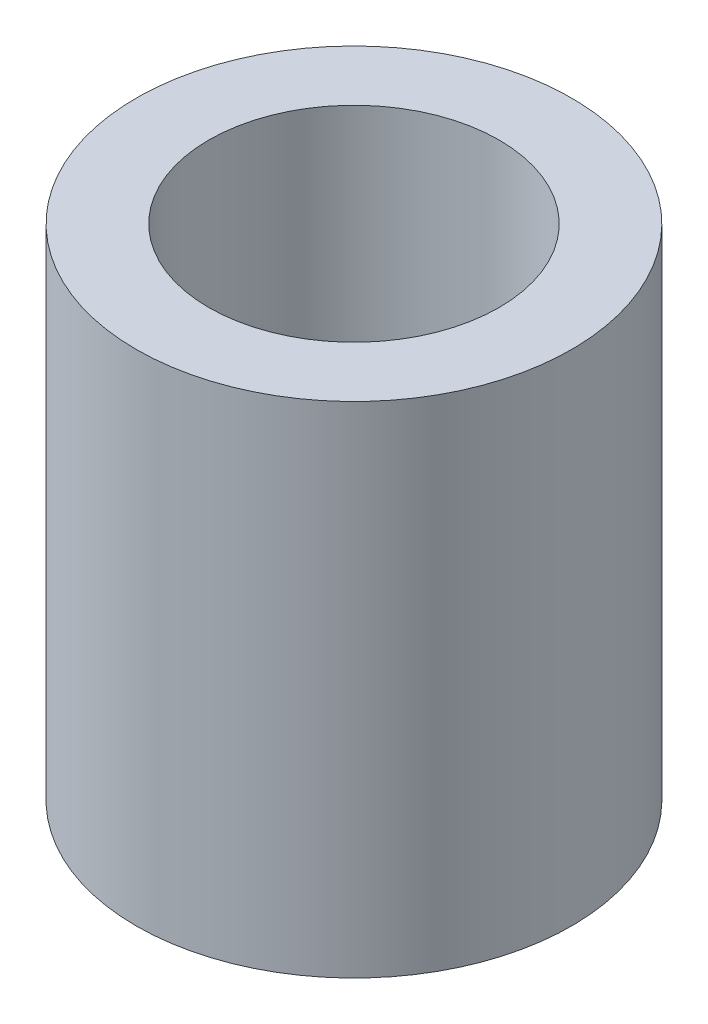
SolidWorks part; units mm, degrees
material "Delrin 2700 NC010, Low Viscosity Acetal Copolymer (SS)"
ref_plane "Front Plane" through (0, 0, 0) normal (0, 0, 1) x (1, 0, 0)
ref_plane "Top Plane" through (0, 0, 0) normal (0, 1, 0) x (1, 0, 0)
ref_plane "Right Plane" through (0, 0, 0) normal (1, 0, 0) x (0, 0, -1)
sketch "Sketch1" plane through (0, 0, 0) normal (0, 1, 0) x (1, 0, 0)
  circle A0 centre (-45.8833, 24.5388) radius 6.35
  circle A1 centre (-45.8833, 24.5388) radius 9.525
  dimension "D1" = 12.7
  dimension "D2" = 19.05
extrude "Boss-Extrude1" add sketch "Sketch1" along normal blind 21.844
